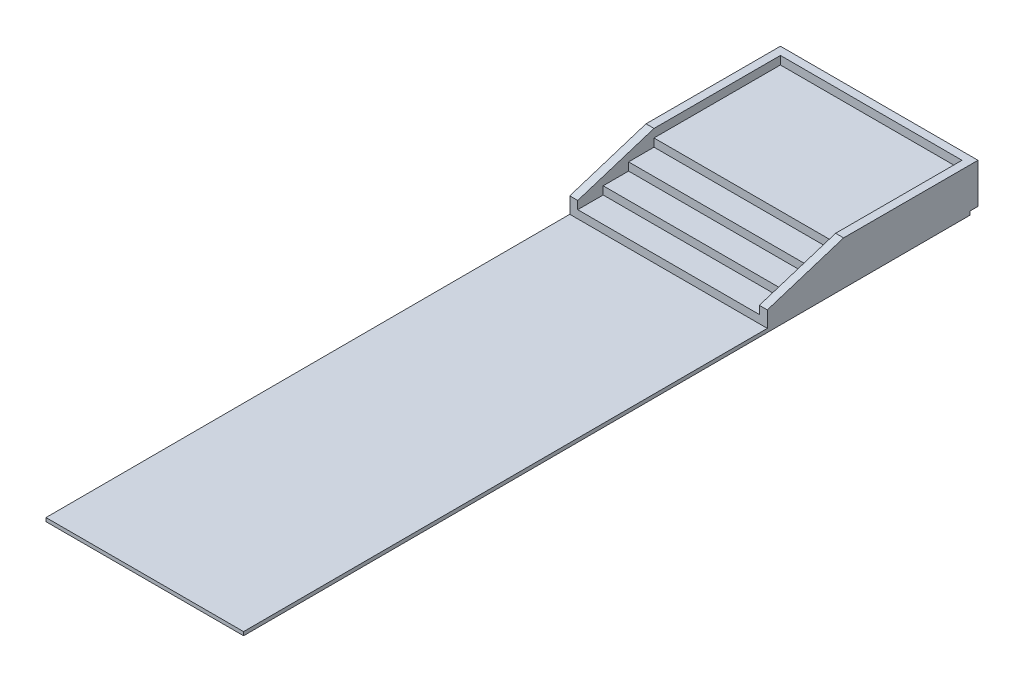
SolidWorks part; units mm, degrees
material "Maple"
ref_plane "Front Plane" through (0, 0, 0) normal (0, 0, 1) x (1, 0, 0)
ref_plane "Top Plane" through (0, 0, 0) normal (0, 1, 0) x (1, 0, 0)
ref_plane "Right Plane" through (0, 0, 0) normal (1, 0, 0) x (0, 0, -1)
sketch "Sketch1" plane through (0, 0, 0) normal (1, 0, 0) x (0, 0, -1)
  line L0 (1.2562, 87.2166) -> (349.2562, 87.2166)
  line L1 (349.2562, 87.2166) -> (349.2562, 0)
  line L2 (1.2562, 87.2166) -> (1.2562, 65.2166)
  line L3 (1.2562, 65.2166) -> (-68.7438, 65.2166)
  line L4 (-68.7438, 65.2166) -> (-68.7438, 43.2166)
  line L5 (-68.7438, 43.2166) -> (-138.7438, 43.2166)
  line L6 (-138.7438, 43.2166) -> (-138.7438, 21.2166)
  line L7 (-138.7438, 21.2166) -> (-208.7438, 21.2166)
  line L8 (-208.7438, 21.2166) -> (-208.7438, -0.7834)
  line L9 (349.2562, 0) -> (-208.7438, -0.7834)
  dimension "D1" = 70
  dimension "D2" = 70
  dimension "D3" = 70
  dimension "D4" = 22
  dimension "D5" = 22
  dimension "D6" = 22
  dimension "D7" = 22
  dimension "D8" = 558
extrude "Boss-Extrude1" add sketch "Sketch1" along normal blind 500
sketch "Sketch2" plane through (500, 0, 0) normal (1, 0, 0) x (0, 0, -1)
  line L0 (-208.7438, -0.7834) -> (-208.7438, 43.2166)
  line L1 (-208.7438, -0.7834) -> (349.2562, 0)
  line L2 (349.2562, 0) -> (371.2562, 0)
  line L3 (371.2562, 0) -> (371.2562, 110)
  line L4 (371.2562, 110) -> (1.2562, 110)
  line L5 (1.2562, 110) -> (-208.7438, 43.2166)
  dimension "D1" = 44
  dimension "D2" = 22
  dimension "D3" = 110
  dimension "D4" = 370
extrude "Boss-Extrude2" add sketch "Sketch2" along normal blind 22
pattern_linear "LPattern1" count 2 spacing 522 along (-1, 0, 0) of "Boss-Extrude2"
sketch "Sketch3" plane through (0, 0, 0) normal (1, 0, 0) x (0, 0, -1)
  line L1 (371.2562, 110) -> (349.2562, 110)
  line L2 (371.2562, 110) -> (371.2562, 0)
  line L3 (371.2562, 0) -> (349.2562, 0)
  line L4 (349.2562, 110) -> (349.2562, 0)
extrude "Boss-Extrude3" add sketch "Sketch3" along normal blind 500
sketch "Sketch4" plane through (0, -0.4904, -0.0007) normal (0, -1, -0.0014) x (1, 0, 0)
  line L1 (522, -349.2559) -> (-22, -349.2559)
  line L2 (522, -349.2559) -> (522, 1650.7441)
  line L3 (522, 1650.7441) -> (-22, 1650.7441)
  line L4 (-22, -349.2559) -> (-22, 1650.7441)
  dimension "D1" = 2000
extrude "Boss-Extrude4" add sketch "Sketch4" along normal blind 10 contours L4 L3 L2 L1
